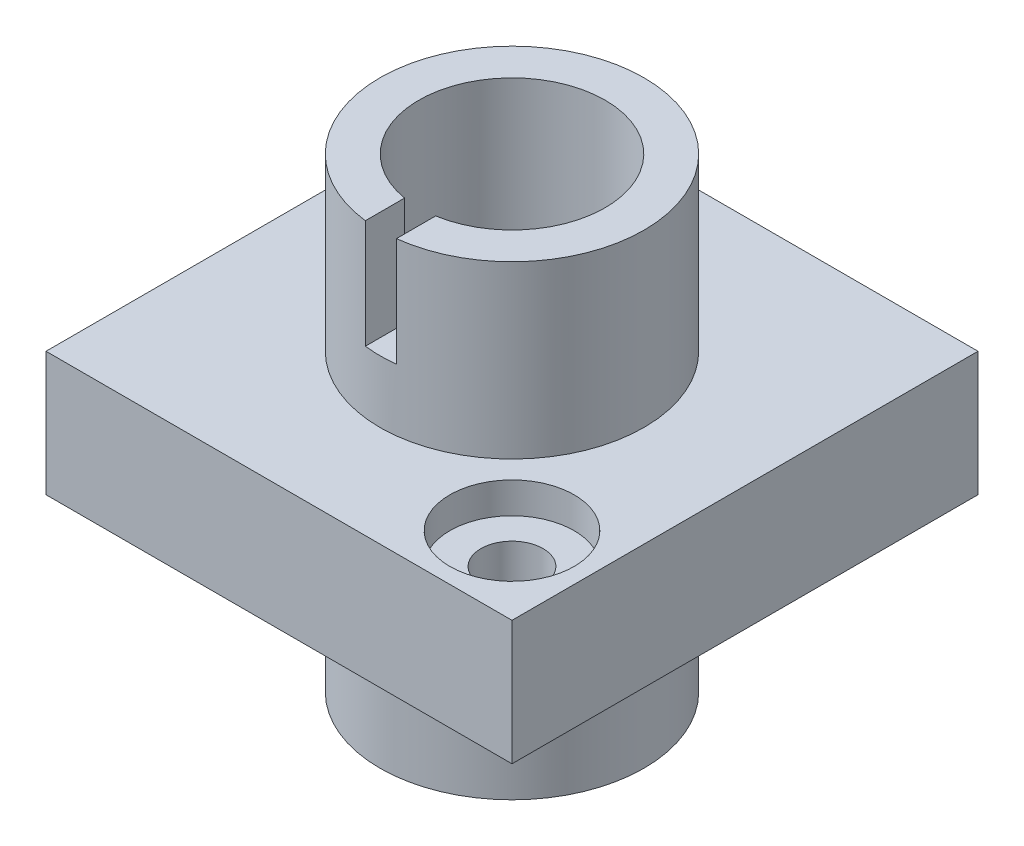
SolidWorks part; units mm, degrees
material "铸造合金钢"
ref_plane "前视基准面" through (0, 0, 0) normal (0, 0, 1) x (1, 0, 0)
ref_plane "上视基准面" through (0, 0, 0) normal (0, 1, 0) x (1, 0, 0)
ref_plane "右视基准面" through (0, 0, 0) normal (1, 0, 0) x (0, 0, -1)
sketch "草图1" plane through (0, 0, 0) normal (0, 1, 0) x (1, 0, 0)
  line L0 (0, 14.3323) -> (0, -15.2472) construction
  line L1 (-15.1496, 0) -> (19.0046, 0) construction
  line L3 (-7.5, 7.5) -> (7.5, 7.5)
  line L4 (-7.5, 7.5) -> (-7.5, -7.5)
  line L5 (-7.5, -7.5) -> (7.5, -7.5)
  line L6 (7.5, 7.5) -> (7.5, -7.5)
  dimension "D1" = 15
  dimension "D2" = 15
extrude "拉伸1" add sketch "草图1" along normal blind 4
sketch "草图2" plane through (0, 4, 0) normal (0, 1, 0) x (-1, 0, 0)
  circle A0 centre (0, 0) radius 4.25
  dimension "D1" = 8.5
extrude "拉伸2" add sketch "草图2" along normal blind 5.5 and the other way offset from surface (9.5 mm away) 5.5 other way up to face at (0, 0, 0)
sketch "草图5" plane through (0, -5.5, 0) normal (0, -1, 0) x (1, 0, 0)
  circle A0 centre (0, 0) radius 3
  dimension "D1" = 6
extrude "切除-拉伸3" cut sketch "草图5" against normal through all
sketch "草图3" plane through (0, 4, 0) normal (0, 1, 0) x (-1, 0, 0)
  line L0 (-10.5791, 0) -> (10.3787, 0) construction
  line L1 (0, 10.0465) -> (0, -11.2778) construction
  line L2 (7.5, 7.5) -> (-7.5, -7.5) construction
  line L3 (-5, -9.226) -> (-5, 10.4861) construction
  line L4 (5, -9.226) -> (5, 10.4861) construction
  line L5 (-5, 9.226) -> (-5, -10.4861) construction
  line L6 (10.8733, -5) -> (-11.1374, -5) construction
  line L7 (10.8733, 5) -> (-11.1374, 5) construction
  circle A0 centre (5, -5) radius 1
  circle A1 centre (-5, 5) radius 1
  dimension "D1" = 10
  dimension "D2" = 10
  dimension "D4" = 2
  dimension "D3" = 2
extrude "切除-拉伸1" cut sketch "草图3" against normal through all
sketch "草图4" plane through (0, 4, 0) normal (0, 1, 0) x (-1, 0, 0)
  circle A10 centre (5, -5) radius 2
  circle A11 centre (5, -5) radius 2
  circle A13 centre (-5, 5) radius 2
  circle A14 centre (-5, 5) radius 2
  dimension "D1" = 1
  dimension "D2" = 1
extrude "切除-拉伸2" cut sketch "草图4" against normal blind 1
sketch "草图6" plane through (0, 9.5, 0) normal (0, 1, 0) x (-1, 0, 0)
  line L0 (0, -1.7556) -> (0, 9.2463) construction
  line L1 (-0.5, 2.177) -> (0.5, 2.177)
  line L2 (-0.5, 2.177) -> (-0.5, 5.1264)
  line L3 (-0.5, 5.1264) -> (0.5, 5.1264)
  line L4 (0.5, 2.177) -> (0.5, 5.1264)
  dimension "D1" = 1
extrude "切除-拉伸4" cut sketch "草图6" against normal offset from surface (3.5 mm away) 2 up to face at (-5, 4, -3)
